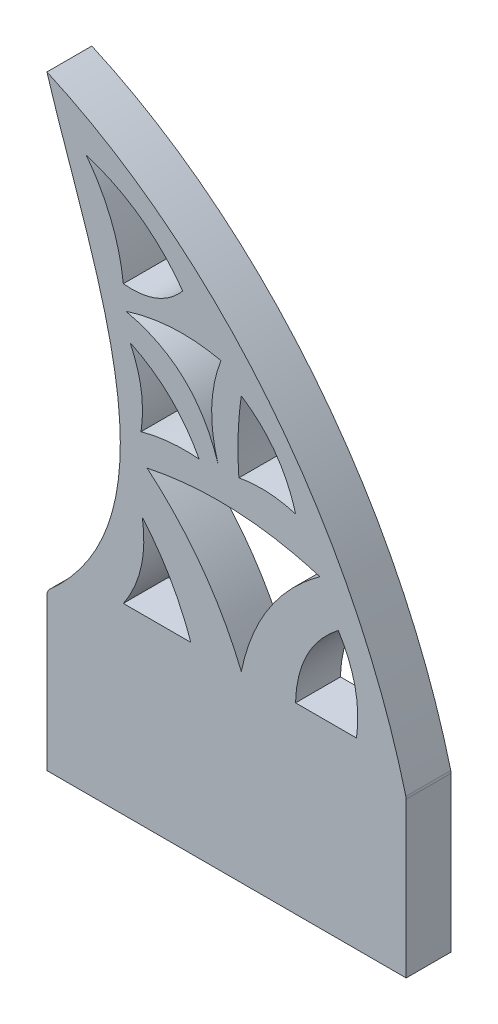
SolidWorks part; units mm, degrees
material "1060 Alloy"
ref_plane "Front Plane" through (0, 0, 0) normal (0, 0, 1) x (1, 0, 0)
ref_plane "Top Plane" through (0, 0, 0) normal (0, 1, 0) x (1, 0, 0)
ref_plane "Right Plane" through (0, 0, 0) normal (1, 0, 0) x (0, 0, -1)
sketch "Sketch1" plane through (0, 0, 0) normal (0, 0, 1) x (1, 0, 0)
  line L1 (0, 0) -> (101.6, 0)
  line L2 (0, 0) -> (0, 152.4)
  line L3 (0, 152.4) -> (101.6, 152.4)
  line L4 (101.6, 0) -> (101.6, 152.4)
  dimension "D1" = 101.6
  dimension "D2" = 152.4
extrude "Boss-Extrude1" add sketch "Sketch1" along normal blind 12.7 contours L2 L1 L4 L3
sketch "Sketch2" plane through (0, 0, 0) normal (0, 0, 1) x (1, 0, 0)
  line L0 (0, 152.4) -> (0, 279.4) construction
  line L1 (0, 152.4) -> (101.6, 152.4)
  line L3 (40.6766, 160.02) -> (21.6029, 160.02)
  line L4 (70.3278, 160.02) -> (87.5465, 160.02)
  spline S0 degree 3 poles (0, 279.4) (51.2861, 256.55) (87.8369, 205.9579) (101.6, 152.4) knots 0 0 0 0 1 1 1 1
  spline S1 degree 3 poles (0, 152.4) (39.7901, 186.8391) (12.3098, 238.8455) (0, 279.4) knots 0 0 0 0 1 1 1 1
  spline S2 degree 2 poles (26.9805, 183.8137) (28.9588, 170.8375) (21.6029, 160.02) knots 0 0 0 1 1 1
  spline S3 degree 2 poles (82.3961, 183.8137) (89.3396, 172.7738) (87.5465, 160.02) knots 0 0 0 1 1 1
  spline S4 degree 2 poles (23.5161, 224.8619) (28.2353, 215.2193) (26.6057, 204.5822) knots 0 0 0 1 1 1
  spline S5 degree 2 poles (54.9771, 227.5573) (66.6459, 219.8522) (70.3283, 206.2775) knots 0 0 0 1 1 1
  spline S6 degree 2 poles (21.6029, 238.3231) (31.8648, 237.2845) (38.4123, 244.9499) knots 0 0 0 1 1 1
  spline S7 degree 2 poles (26.9805, 183.8137) (36.1385, 173.1751) (40.6766, 160.02) knots 0 0 0 1 1 1
  spline S8 degree 2 poles (82.3961, 183.8137) (70.6714, 174.6636) (70.3278, 160.02) knots 0 0 0 1 1 1
  spline S9 degree 2 poles (54.9771, 160.02) (46.0835, 181.5476) (28.3421, 196.5298) knots 0 0 0 1 1 1
  spline S10 degree 2 poles (54.9771, 160.02) (59.3747, 181.4006) (77.1872, 194.3635) knots 0 0 0 1 1 1
  spline S11 degree 2 poles (28.3421, 196.5298) (53.0178, 201.7323) (77.1872, 194.3635) knots 0 0 0 1 1 1
  spline S12 degree 2 poles (26.6057, 204.5822) (34.7004, 206.7929) (43.0535, 206.088) knots 0 0 0 1 1 1
  spline S13 degree 2 poles (43.0535, 206.088) (36.2398, 218.9127) (23.5161, 224.8619) knots 0 0 0 1 1 1
  spline S14 degree 2 poles (70.3283, 206.2775) (62.3616, 208.669) (54.2871, 207.1099) knots 0 0 0 1 1 1
  spline S15 degree 2 poles (54.2871, 207.1099) (53.4821, 217.3917) (54.9771, 227.5573) knots 0 0 0 1 1 1
  spline S16 degree 2 poles (48.4004, 207.5354) (42.0542, 227.5662) (22.3756, 231.9373) knots 0 0 0 1 1 1
  spline S17 degree 2 poles (48.4004, 207.5354) (44.3936, 220.7345) (49.2258, 233.3158) knots 0 0 0 1 1 1
  spline S18 degree 2 poles (49.2258, 233.3158) (35.6412, 236.2679) (22.3756, 231.9373) knots 0 0 0 1 1 1
  spline S19 degree 2 poles (21.6029, 238.3231) (19.952, 252.9745) (11.0947, 264.6015) knots 0 0 0 1 1 1
  spline S20 degree 2 poles (11.0947, 264.6015) (28.0538, 259.2958) (38.4123, 244.9499) knots 0 0 0 1 1 1
  dimension "D1" = 127
extrude "Boss-Extrude3" add sketch "Sketch2" along normal blind 12.7 contours S1 L1 S0 S18 S17 S16 S13 S12 S4 S8 S3 L4 S2 S7 L3 S9 S11 S10 S14 S15 S5 S19 S20 S6
fillet "Fillet1" radius 2.54 2 edges at (101.6, 152.4, 6.35) (0, 152.4, 6.35)
fillet "Fillet2" radius 5.08 2 edges at (101.6, 0, 6.35) (0, 0, 6.35)
sketch "Sketch3" plane through (0, 0, 12.7) normal (0, 0, 1) x (1, 0, 0)
  line L0 (101.519, 152.714) -> (101.519, 108.264) construction
  dimension "D1" = 44.45
sketch "Sketch4" plane through (0, 0, 12.7) normal (0, 0, 1) x (1, 0, 0)
  line L0 (101.519, 108.264) -> (0, 108.264)
  line L1 (0, 5.08) -> (0, 151.2513) construction
  line L2 (101.519, 108.264) -> (101.6, 108.264)
  line L3 (101.6, 5.08) -> (101.6, 152.0778) construction
  line L4 (101.6, 108.264) -> (101.6, 0)
  line L5 (101.6, 0) -> (0, 0)
  line L6 (0, 0) -> (0, 108.264)
extrude "Cut-Extrude1" cut sketch "Sketch4" against normal through all
